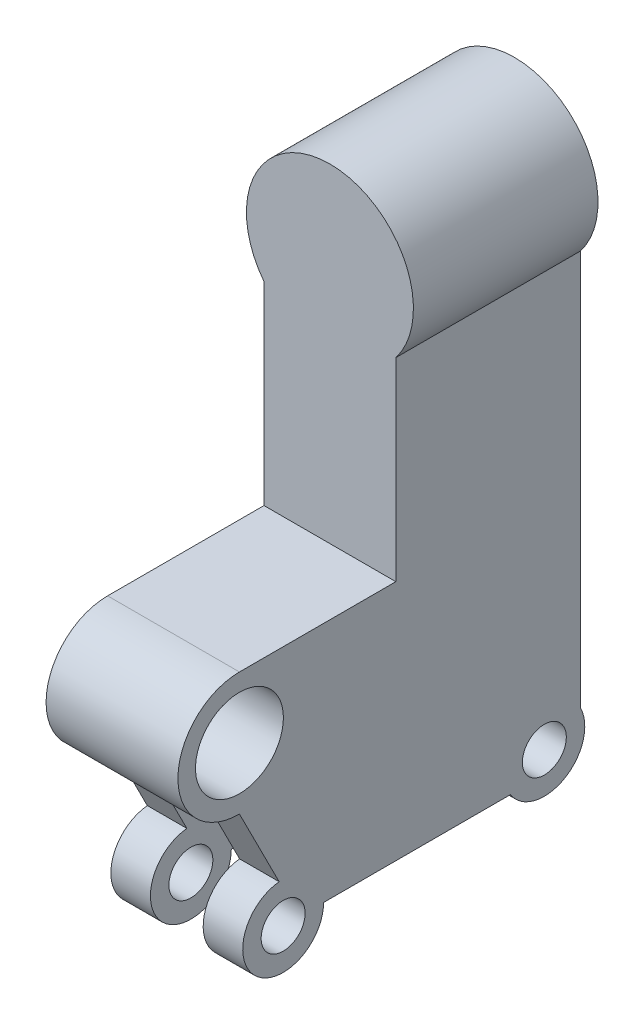
SolidWorks part; units mm, degrees
material "AISI 1045 Steel, cold drawn"
ref_plane "Ön Düzlem" through (0, 0, 0) normal (0, 0, 1) x (1, 0, 0)
ref_plane "Üst Düzlem" through (0, 0, 0) normal (0, 1, 0) x (1, 0, 0)
ref_plane "Sağ Düzlem" through (0, 0, 0) normal (1, 0, 0) x (0, 0, -1)
sketch "Sketch1" plane through (0, 0, 0) normal (1, 0, 0) x (0, 0, -1)
  line L0 (0, -7) -> (4.5149, -15.9228)
  line L1 (9.572, -20.5) -> (30.8264, -20.5)
  line L2 (38.7921, -15.9228) -> (38.7921, 29.0772)
  line L3 (0, 7) -> (17.7921, 7)
  line L4 (17.7921, 7) -> (17.7921, 29.0772)
  line L5 (17.7921, 29.0772) -> (38.7921, 29.0772)
  circle A0 centre (0, 0) radius 5
  circle A1 centre (4.972, -20.5) radius 2.5
  circle A2 centre (34.6878, -18) radius 2.5
  arc A4 (0, 7) -> (0, -7) centre (0, 0) ccw
  arc A6 (4.5149, -15.9228) -> (9.572, -20.5) centre (4.972, -20.5) ccw
  arc A7 (30.8264, -20.5) -> (38.7921, -15.9228) centre (34.6878, -18) ccw
  dimension "D1" = 10
  dimension "D2" = 5
  dimension "D3" = 5
  dimension "D4" = 14
  dimension "D5" = 21.2545
  dimension "D6" = 9.2
  dimension "D14" = 9.2
  dimension "D7" = 45
  dimension "D8" = 21
  dimension "D9" = 38.7921
  dimension "D10" = 10
  dimension "D11" = 20.5
  dimension "D12" = 18
extrude "Boss-Extrude2" add sketch "Sketch1" along normal blind 15
sketch "Sketch2" plane through (0, -20.5, 0) normal (0, -1, 0) x (1, 0, 0)
  line L0 (4.5, -0.372) -> (4.5, -39.2878)
  line L3 (4.5, -39.2878) -> (10.5, -39.2878)
  line L4 (10.5, -39.2878) -> (10.5, -0.372)
  line L5 (10.5, -0.372) -> (4.5, -0.372)
  line L7 (0, -39.2878) -> (15, -39.2878) construction
  line L8 (15, -0.372) -> (0, -0.372) construction
  dimension "D1" = 6
  dimension "D2" = 4.5
sketch "Sketch3" plane through (0, 0, 0) normal (-1, 0, 0) x (0, 0, 1)
  circle A0 centre (-4.972, -20.5) radius 4.6
  circle A1 centre (-4.972, -20.5) radius 2.5
  dimension "D1" = 5
  dimension "D2" = 9.2
sketch "Sketch4" plane through (15, 0, 0) normal (1, 0, 0) x (0, 0, -1)
  circle A0 centre (34.6878, -18) radius 2.5
  circle A2 centre (34.6878, -18) radius 4.6
  dimension "D1" = 5
  dimension "D2" = 9.2
extrude "Cut-Extrude1" cut sketch "Sketch2" against normal blind 11
extrude "Cut-Extrude2" cut sketch "Sketch3" against normal blind 6 from offset 4.5 offset against normal yes
extrude "Cut-Extrude3" cut sketch "Sketch4" against normal blind 6 from offset 4.5 offset against normal yes
sketch "Sketch6" plane through (0, 0, -38.7921) normal (0, 0, -1) x (-1, 0, 0)
  line L0 (-15, 29.0772) -> (0, 29.0772)
  arc A0 (-15, 29.0772) -> (0, 29.0772) centre (-7.5, 34.9082) cw
  circle A1 centre (-7.5, 34.9082) radius 6
  line M7 (0, 29.0772) -> (-15, 29.0772)
  dimension "D1" = 9.5
  dimension "D2" = 12
extrude "Boss-Extrude3" add sketch "Sketch6" against normal up to surface (21 mm away) contours A1 A0 M7
sketch "Sketch7" plane through (0, 0, -38.7921) normal (0, 0, -1) x (-1, 0, 0)
  line L0 (-8.9142, 29.0772) -> (-6.0858, 29.0772)
  arc A0 (-8.9142, 29.0772) -> (-6.0858, 29.0772) centre (-7.5, 34.9082) ccw
  dimension "D1" = 6
extrude "Cut-Extrude4" cut sketch "Sketch7" against normal through all
sketch "Sketch8" plane through (0, 0, -38.7921) normal (0, 0, -1) x (-1, 0, 0)
  circle A0 centre (-7.5, 34.9082) radius 6
  circle A1 centre (-7.5, 34.9082) radius 6 construction
extrude "Boss-Extrude4" add sketch "Sketch8" against normal up to surface (5.5 mm away) from offset 15.5 up to face at (7.5, 21.8714, -17.7921) offset against normal yes
